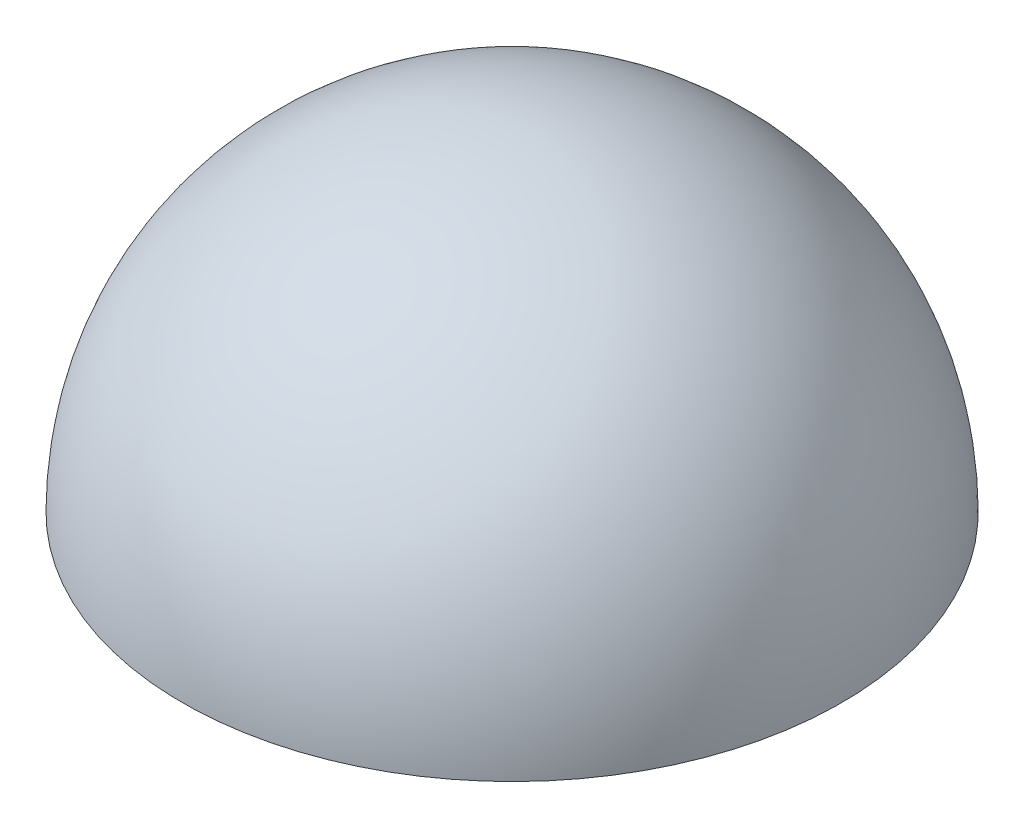
SolidWorks part; units mm, degrees
ref_plane "Front Plane" through (0, 0, 0) normal (0, 0, 1) x (1, 0, 0)
ref_plane "Top Plane" through (0, 0, 0) normal (0, 1, 0) x (1, 0, 0)
ref_plane "Right Plane" through (0, 0, 0) normal (1, 0, 0) x (0, 0, -1)
sketch "Sketch1" plane through (0, 0, 0) normal (0, 1, 0) x (1, 0, 0)
  line L0 (-5, 0) -> (5, 0)
  arc A0 (5, 0) -> (-5, 0) centre (0, 0) ccw
  dimension "D1" = 10
revolve "Revolve2" add sketch "Sketch1" angle 180 about L0
sketch "Sketch2" plane through (0, 0, 0) normal (0, -1, 0) x (1, 0, 0)
  line L0 (-4.5, 0) -> (4.5, 0)
  arc A0 (4.5, 0) -> (-4.5, 0) centre (0, 0) ccw
  dimension "D1" = 9
revolve "Cut-Revolve1" cut sketch "Sketch2" angle 180 about L0
